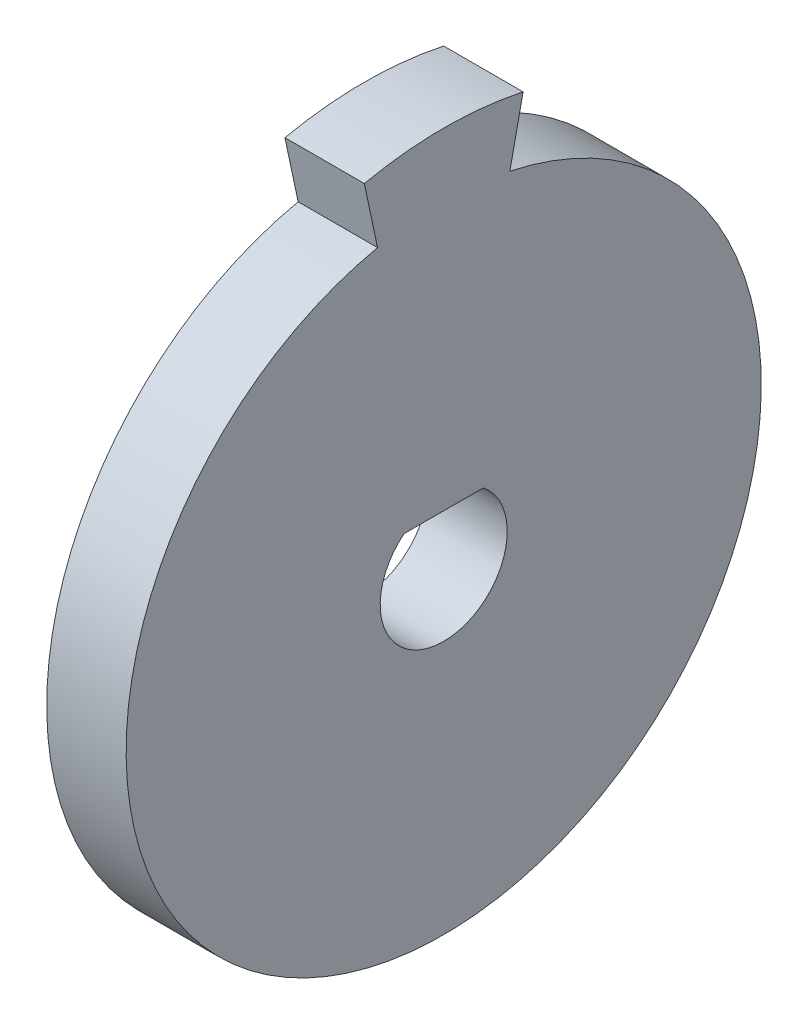
SolidWorks part; units mm, degrees
material "AISI 304"
ref_plane "Plan de face" through (0, 0, 0) normal (0, 0, 1) x (1, 0, 0)
ref_plane "Plan de dessus" through (0, 0, 0) normal (0, 1, 0) x (1, 0, 0)
ref_plane "Plan de droite" through (0, 0, 0) normal (1, 0, 0) x (0, 0, -1)
sketch "Sketch1" plane through (0, 0, 0) normal (1, 0, 0) x (0, 0, -1)
  line L0 (-3.175, 3.9656) -> (3.175, 3.9656)
  circle A0 centre (0, 0) radius 25.4
  arc A1 (-3.175, 3.9656) -> (3.175, 3.9656) centre (0, 0) ccw
  dimension "D1" = 50.8
  dimension "D3" = 10.16
  dimension "D2" = 6.35
extrude "Boss-Extrude1" add sketch "Sketch1" along normal mid plane 6.35
sketch "Sketch2" plane through (0, 0, 0) normal (1, 0, 0) x (0, 0, -1)
  line L0 (-5.2917, 24.8427) -> (-6.35, 29.8112)
  line L1 (0, 55) -> (0, -55) construction
  line L2 (5.2917, 24.8427) -> (6.35, 29.8112)
  arc A0 (6.35, 29.8112) -> (-6.35, 29.8112) centre (0, 0) ccw
  circle A1 centre (0, 0) radius 25.4 construction
  arc A2 (5.2917, 24.8427) -> (-5.2917, 24.8427) centre (0, 0) ccw
  dimension "D2" = 12.7
  dimension "D1" = 5.08
extrude "Boss-Extrude2" add sketch "Sketch2" along normal mid plane 6.35
